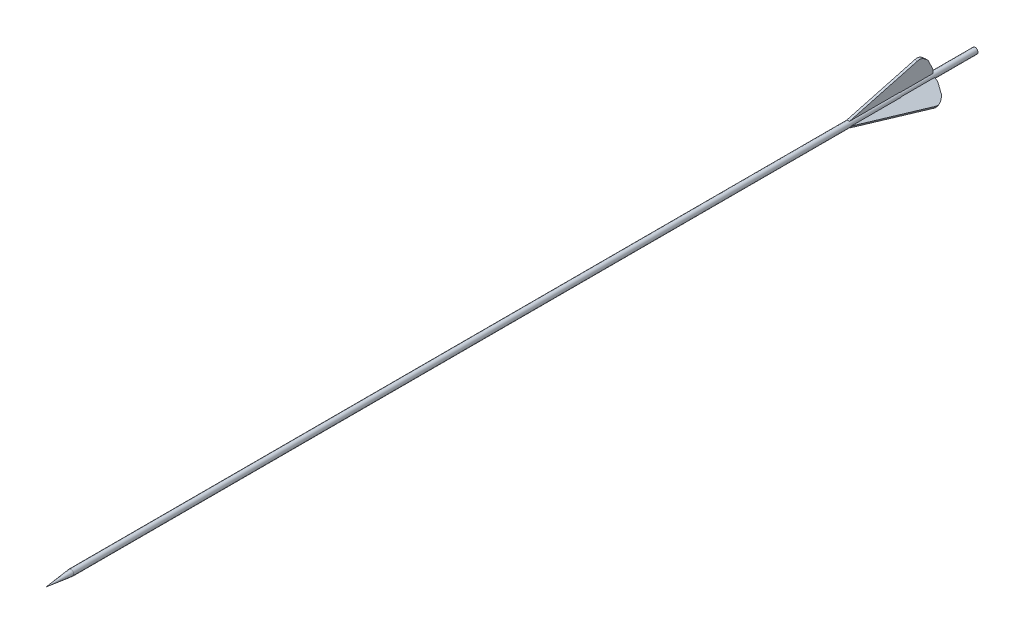
SolidWorks part; units mm, degrees
ref_plane "Front Plane" through (0, 0, 0) normal (0, 0, 1) x (1, 0, 0)
ref_plane "Top Plane" through (0, 0, 0) normal (0, 1, 0) x (1, 0, 0)
ref_plane "Right Plane" through (0, 0, 0) normal (1, 0, 0) x (0, 0, -1)
sketch "Sketch1" plane through (0, 0, 0) normal (1, 0, 0) x (0, 0, -1)
  line L0 (-365.7474, 0) -> (365.7474, 0) construction
  line L2 (-346.1252, 2.2352) -> (365.8519, 2.2352)
  line L3 (365.8519, 2.2352) -> (365.7474, 0)
  line L4 (-365.7474, 0) -> (365.7474, 0)
  line L5 (-340.3474, 0) -> (-340.3474, 32.5393) construction
  line L6 (-365.7474, 0) -> (-346.1252, 2.2352)
  point P3 (0, 0)
  dimension "D2" = 711.2
  dimension "D1" = 2.2352
  dimension "D3" = 25.4
revolve "Revolve1" add sketch "Sketch1" angle 360 about L0
sketch "Sketch3" plane through (0, 0, 0) normal (1, 0, 0) x (0, 0, -1)
  line L0 (365.8519, 2.2352) -> (-346.1252, 2.2352) construction
  line L1 (304.5951, 2.2352) -> (265.8519, 2.2352)
  line L2 (265.8519, 2.2352) -> (265.8519, 75.5182) construction
  line L3 (265.8519, 2.2352) -> (319.4386, 16.5937)
  arc A0 (324.7682, 15.4605) -> (319.4386, 16.5937) centre (320.9916, 10.7982) ccw
  spline S0 degree 3 poles (304.5951, 2.2352) (317.619, 0.0748) (336.8344, -3.6983) (326.7899, 13.8683) (329.1837, 11.8838) (324.7682, 15.4605) knots 0 0 0 0 0.505374 0.593785 0.884112 0.884112 0.884112 0.884112
  point P9 (0, 0)
  point P10 (319.9365, 9.7606)
  point P11 (0, 0)
  point P12 (0, 0)
  point P13 (312.3384, 9.7606)
  point P14 (0, 0)
  point P15 (322.7115, 10.8465)
  point P16 (0, 0)
  point P17 (324.5213, 5.5378)
  point P18 (309.7659, 12.3733)
  point P19 (318.6169, 20.8395)
  point P20 (327.6604, 9.9681)
  point P21 (303.6582, 14.6083)
  point P22 (316.4175, 10.8967)
  point P24 (320.9916, 10.8967)
  point P25 (329.5622, 10.0173)
  point P26 (0, 0)
  point P27 (0, 0)
  point P28 (0, 0)
  point P29 (0, 0)
  point P30 (0, 0)
  point P31 (0, 0)
  point P32 (0, 0)
  point P33 (0, 0)
  point P34 (0, 0)
  point P35 (0, 0)
  point P36 (328.0603, 9.392)
  point P37 (329.6896, 10.0167)
  point P38 (329.7132, 9.6971)
  point P39 (0, 0)
  point P40 (0, 0)
  point P41 (0, 0)
  point P42 (330.2489, 7.8175)
  dimension "D3" = 6
  dimension "D1" = 100
  dimension "D2" = 15
extrude "Boss-Extrude1" add sketch "Sketch3" along normal mid plane 2 separate body
pattern_circular "CirPattern5" count 3 over 360 about axis through (0, 0, -365.7474) along (0, 0, -1) of bodies 102
